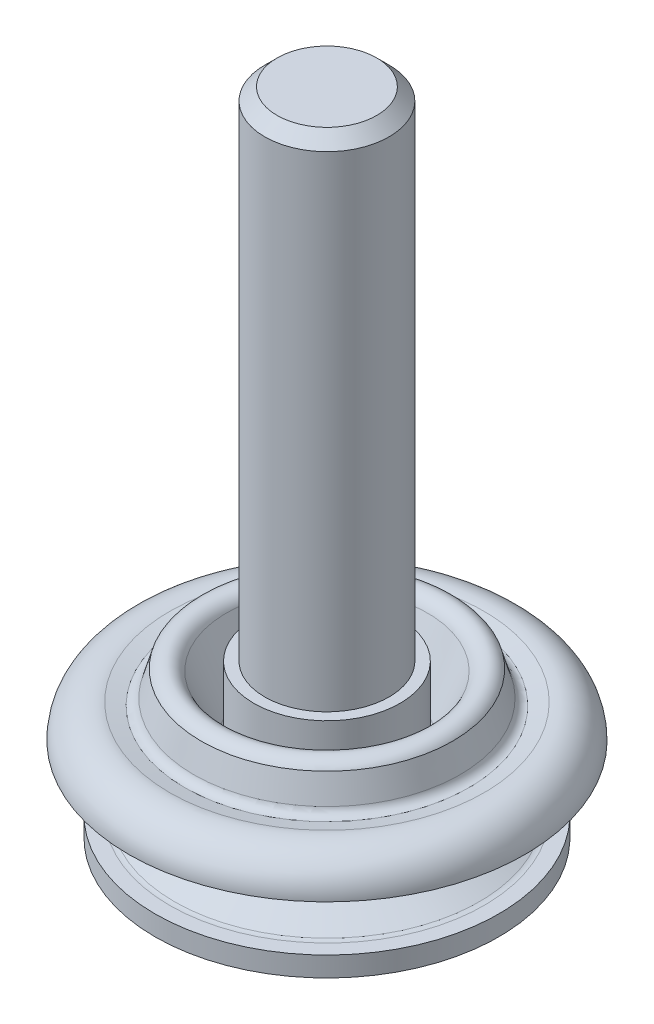
SolidWorks part; units mm, degrees
ref_plane "Front Plane" through (0, 0, 0) normal (0, 0, 1) x (1, 0, 0)
ref_plane "Top Plane" through (0, 0, 0) normal (0, 1, 0) x (1, 0, 0)
ref_plane "Right Plane" through (0, 0, 0) normal (1, 0, 0) x (0, 0, -1)
ref_plane "Plane1" through (0, 0, 0.3194) normal (0, 0, -1) x (-1, 0, 0)
sketch "Sketch1" plane through (0, 0, 0.3194) normal (0, 0, -1) x (-1, 0, 0)
  line L0 (5.2199, 23.3071) -> (10.8805, 23.3071)
  line L1 (10.8805, 23.3071) -> (10.8805, 70.2332)
  line L2 (10.8805, 70.2332) -> (7.0642, 70.2332)
  line L3 (7.0642, 70.2332) -> (6.118, 69.2871)
  line L4 (6.118, 69.2871) -> (6.118, 32.1332)
  line L5 (6.118, 32.1332) -> (5.2785, 32.1332)
  line L6 (5.2785, 32.1332) -> (5.2785, 27.0205)
  line L7 (5.0455, 27.1733) -> (3.178, 31.4738)
  line L8 (1.2526, 31.6346) -> (0.6887, 29.6891)
  line L9 (0.0021, 29.1733) -> (-1.1571, 29.4216)
  line L10 (-4.2907, 26.8883) -> (-2.7667, 26.8883)
  line L11 (-0.6331, 26.8883) -> (0.0021, 26.8883)
  line L12 (0.9698, 27.4936) -> (2.1721, 29.9641)
  line L13 (2.1721, 29.9641) -> (3.5362, 26.4527)
  line L14 (4.3422, 25.8471) -> (4.1023, 25.8471)
  line L15 (4.1023, 25.8471) -> (4.0567, 24.6836)
  line L16 (3.6947, 24.1348) -> (-0.7897, 22.0045)
  line L17 (-1.1571, 21.9427) -> (-2.2807, 21.9427)
  line L18 (-2.2807, 21.9427) -> (-2.2807, 20.4187)
  line L19 (-2.2807, 20.4187) -> (-0.8624, 20.4187)
  line L20 (-0.3174, 20.5416) -> (4.3487, 22.7583)
  line L21 (6.1148, 24.7147) -> (5.2199, 23.3071)
  line L22 (10.8805, 20.4187) -> (10.8805, 70.2332) construction
  arc A0 (5.2785, 27.0205) -> (5.0455, 27.1733) centre (5.2785, 27.2745) cw
  arc A1 (3.178, 31.4738) -> (1.2526, 31.6346) centre (2.1721, 31.0369) ccw
  arc A2 (0.6887, 29.6891) -> (0.0021, 29.1733) centre (0.0021, 29.8881) cw
  arc A3 (-1.1571, 29.4216) -> (-4.2907, 26.8883) centre (-1.6999, 26.8883) ccw
  arc A4 (-2.7667, 26.8883) -> (-0.6331, 26.8883) centre (-1.6999, 26.8883) ccw
  arc A5 (0.0021, 26.8883) -> (0.9698, 27.4936) centre (0.0021, 27.9646) ccw
  arc A6 (3.5362, 26.4527) -> (4.3422, 25.8471) centre (4.3422, 26.6862) ccw
  arc A7 (4.0567, 24.6836) -> (3.6947, 24.1348) centre (3.4222, 24.7084) cw
  arc A8 (-0.7897, 22.0045) -> (-1.1571, 21.9427) centre (-1.1571, 23.0663) cw
  arc A9 (-0.8624, 20.4187) -> (-0.3174, 20.5416) centre (-0.8624, 21.6887) ccw
  arc A10 (4.3487, 22.7583) -> (5.5435, 24.3064) centre (3.4222, 24.7084) ccw
  arc A11 (5.5435, 24.3064) -> (6.1148, 24.7147) centre (6.0426, 24.2118) cw
revolve "Revolve1" add sketch "Sketch1" angle 360 about L22
